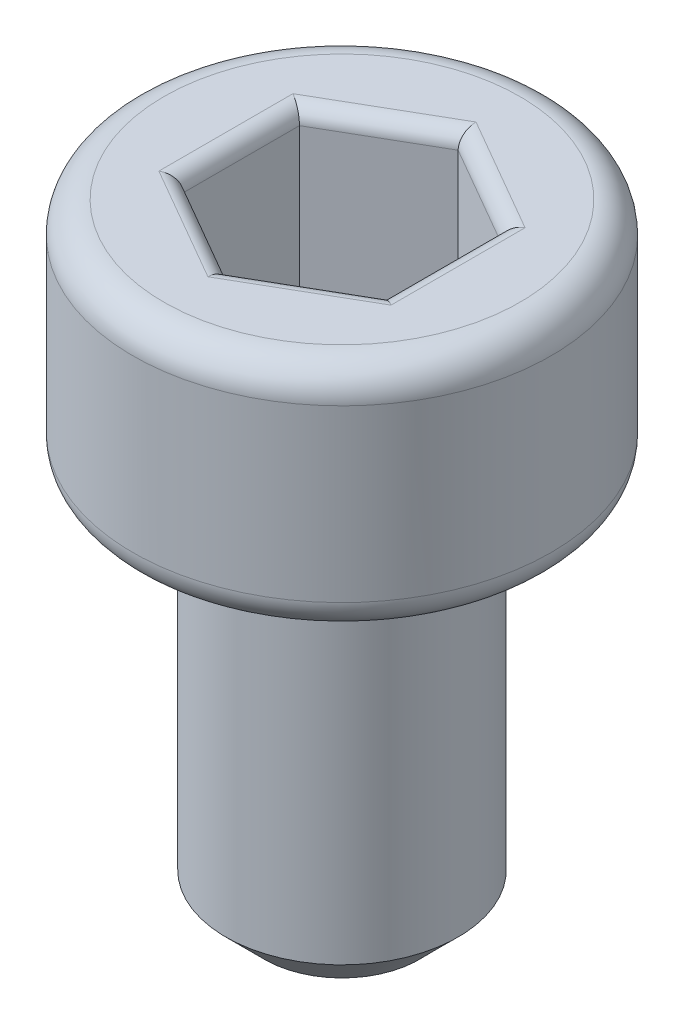
SolidWorks part; units mm, degrees
ref_plane "Ebene vorne" through (0, 0, 0) normal (0, 0, 1) x (1, 0, 0)
ref_plane "Ebene oben" through (0, 0, 0) normal (0, 1, 0) x (1, 0, 0)
ref_plane "Ebene rechts" through (0, 0, 0) normal (1, 0, 0) x (0, 0, -1)
sketch "Skizze1" plane through (0, 0, 0) normal (0, 0, 1) x (1, 0, 0)
  line L0 (0, 0) -> (0, -8)
  line L1 (0, -8) -> (-1, -8)
  line L4 (-1.5, -3) -> (-2.7, -3)
  line L5 (-2.7, -3) -> (-2.7, 0)
  line L6 (-2.7, 0) -> (0, 0)
  line L7 (-1.5, -7.5) -> (-1, -8)
  line L8 (-1.5, -7.5) -> (-1.5, -3)
  dimension "D1" = 2.7
  dimension "D2" = 3
  dimension "D3" = 1
  dimension "D4" = 5
  dimension "D5" = 1.5
  dimension "D7" = 135
revolve "Rotation1" add sketch "Skizze1" angle 360 about L0
sketch "Skizze2" plane through (0, 0, 0) normal (0, 1, 0) x (1, 0, 0)
  line L0 (1.299, 0.75) -> (1.299, -0.75)
  line L1 (1.299, -0.75) -> (0, -1.5)
  line L2 (0, -1.5) -> (-1.299, -0.75)
  line L3 (-1.299, -0.75) -> (-1.299, 0.75)
  line L4 (-1.299, 0.75) -> (0, 1.5)
  line L5 (0, 1.5) -> (1.299, 0.75)
  line L6 (0, -1.5) -> (0, 1.5) construction
  circle A0 centre (0, 0) radius 1.5 construction
  dimension "D1" = 3
extrude "Schnitt-Linear austragen1" cut sketch "Skizze2" against normal blind 2
fillet "Verrundung1" radius 0.4 2 edges at (-2.7, -3, 0) (-2.7, 0, 0)
fillet "Verrundung2" radius 0.2 6 edges at (-0.6495, 0, -1.125) (-1.299, 0, 0) (-0.6495, 0, 1.125) (0.6495, 0, 1.125) (1.299, 0, 0) (0.6495, 0, -1.125)
